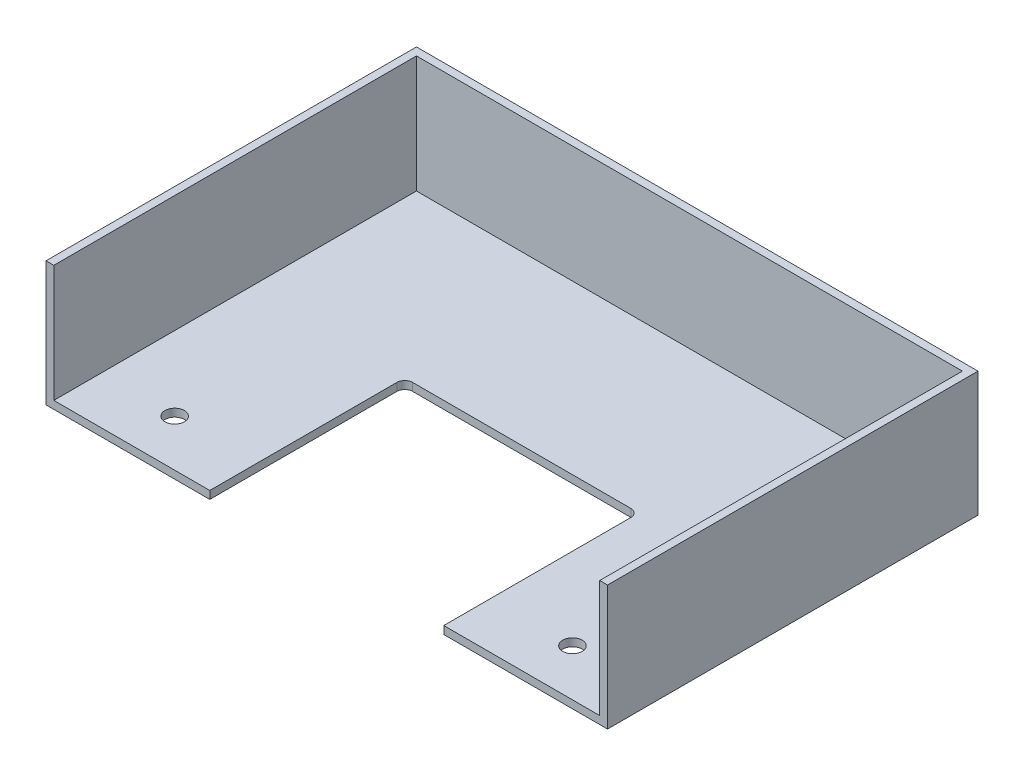
SolidWorks part; units mm, degrees
ref_plane "前视基准面" through (0, 0, 0) normal (0, 0, 1) x (1, 0, 0)
ref_plane "上视基准面" through (0, 0, 0) normal (0, 1, 0) x (1, 0, 0)
ref_plane "右视基准面" through (0, 0, 0) normal (1, 0, 0) x (0, 0, -1)
other "Configuration Table"
ref_plane "基准面1" through (0, 0, 0) normal (0, -1, 0) x (1, 0, 0)
sketch "草图1" plane through (0, 0, 0) normal (0, -1, 0) x (1, 0, 0)
  line L0 (72, 47.5) -> (-72, 47.5)
  line L1 (-72, 47.5) -> (-72, -47.5)
  line L2 (-72, -47.5) -> (72, -47.5)
  line L3 (72, -47.5) -> (72, 47.5)
extrude "凸台-拉伸1" add sketch "草图1" against normal blind 32
sketch "草图2" plane through (0, 32, 0) normal (0, 1, 0) x (-1, 0, 0)
  line L0 (-70, 47.5) -> (-70, -45.5)
  line L1 (-70, -45.5) -> (70, -45.5)
  line L2 (70, -45.5) -> (70, 47.5)
  line L3 (70, 47.5) -> (-70, 47.5)
extrude "切除-拉伸1" cut sketch "草图2" against normal blind 30
sketch "草图3" plane through (0, 0, 0) normal (0, -1, 0) x (1, 0, 0)
  line L0 (30, 47.5) -> (-30, 47.5)
  line L1 (-30, 47.5) -> (-30, -0.5)
  line L2 (-28, -2.5) -> (28, -2.5)
  line L3 (30, -0.5) -> (30, 47.5)
  arc A0 (-30, -0.5) -> (-28, -2.5) centre (-28, -0.5) ccw
  arc A1 (28, -2.5) -> (30, -0.5) centre (28, -0.5) ccw
extrude "切除-拉伸2" cut sketch "草图3" against normal through all
hole_wizard "Ø5.0 (5) 直径孔1" positions "草图5" profile "草图4" hole size "Ø5.0" standard "ANSI Metric"
sketch "草图5" plane through (0, 2, 0) normal (0, 1, 0) x (1, 0, 0)
  point P0 (51, -35.5)
  point P1 (-51, -35.5)
sketch "草图4" plane through (51, 2, 35.5) normal (1, 0, 0) x (0, 0, 1)
  line L0 (0, 0) -> (0, 2)
  line L1 (0, 2) -> (2.5, 2)
  line L2 (2.5, 2) -> (2.5, 0)
  line L5 (2.5, 0) -> (0, 0)
  line L11 (0, -6.35) -> (0, 107.95) construction
  dimension "通孔孔直径" = 5
  dimension "通孔孔深度" = 2
